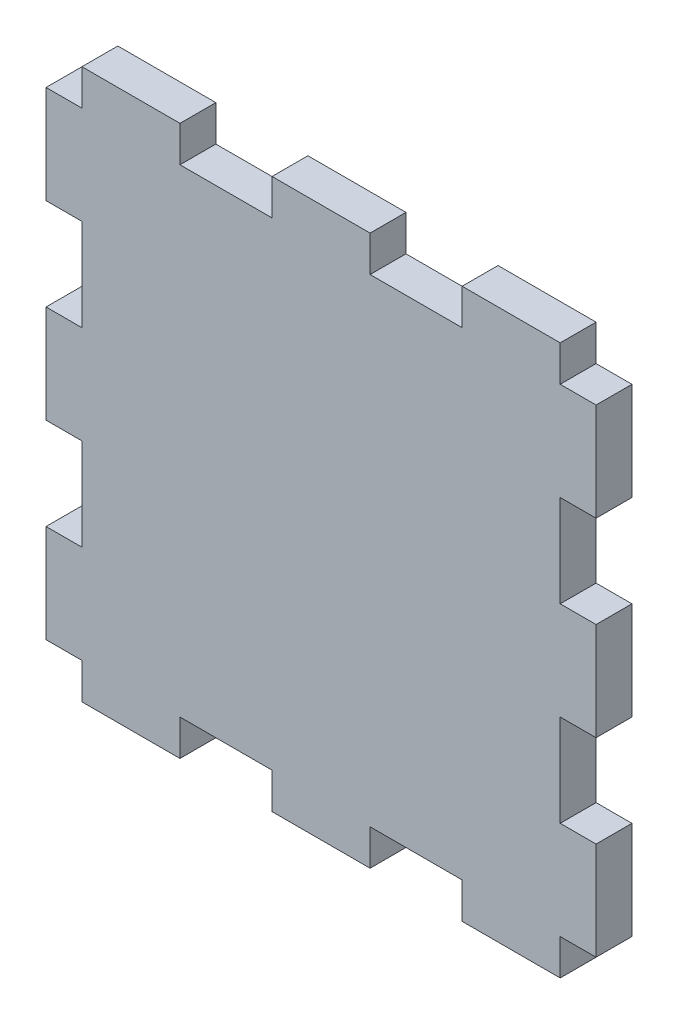
SolidWorks part; units mm, degrees
ref_plane "Alzado" through (0, 0, 0) normal (0, 0, 1) x (1, 0, 0)
ref_plane "Planta" through (0, 0, 0) normal (0, 1, 0) x (1, 0, 0)
ref_plane "Vista lateral" through (0, 0, 0) normal (1, 0, 0) x (0, 0, -1)
sketch "Croquis1" plane through (0, 0, 0) normal (0, 0, 1) x (1, 0, 0)
  line L0 (0, 0) -> (0, 16.0174) construction
  line L1 (20, -20) -> (-20, -20)
  line L2 (20, -20) -> (20, 20)
  line L3 (20, 20) -> (-20, 20)
  line L4 (-20, -20) -> (-20, 20)
  line L5 (20, -20) -> (-20, 20) construction
  line L6 (20, 20) -> (-20, -20) construction
  line L7 (-20, 20) -> (-23, 20)
  line L8 (-20, 20) -> (-20, 11.8)
  line L9 (-20, 11.8) -> (-23, 11.8)
  line L10 (-23, 20) -> (-23, 11.8)
  line L11 (-20, -20) -> (-23, -20)
  line L12 (-20, -20) -> (-20, -11.8)
  line L13 (-20, -11.8) -> (-23, -11.8)
  line L14 (-23, -20) -> (-23, -11.8)
  line L15 (-20, -4.1) -> (-23, -4.1)
  line L16 (-20, -4.1) -> (-20, 4.1)
  line L17 (-20, 4.1) -> (-23, 4.1)
  line L18 (-23, -4.1) -> (-23, 4.1)
  line L19 (-20, -20) -> (-11.8, -20)
  line L20 (-20, -20) -> (-20, -23.0026)
  line L21 (-20, -23.0026) -> (-11.8, -23.0026)
  line L22 (-11.8, -20) -> (-11.8, -23.0026)
  line L23 (-4.1, -20) -> (4.1, -20)
  line L24 (-4.1, -20) -> (-4.1, -23.0026)
  line L25 (-4.1, -23.0026) -> (4.1, -23.0026)
  line L26 (4.1, -20) -> (4.1, -23.0026)
  line L27 (20, -20) -> (11.8, -20)
  line L28 (20, -20) -> (20, -23.0026)
  line L29 (20, -23.0026) -> (11.8, -23.0026)
  line L30 (11.8, -20) -> (11.8, -23.0026)
  line L31 (0, 16.0174) -> (0, 0) construction
  line L32 (0, 0) -> (-15.6024, 0) construction
  line L33 (20, 23.0026) -> (11.8, 23.0026)
  line L34 (11.8, 20) -> (11.8, 23.0026)
  line L35 (20, 20) -> (11.8, 20)
  line L36 (20, 20) -> (20, 23.0026)
  line L37 (-4.1, 23.0026) -> (4.1, 23.0026)
  line L38 (4.1, 20) -> (4.1, 23.0026)
  line L39 (-4.1, 20) -> (4.1, 20)
  line L40 (-4.1, 20) -> (-4.1, 23.0026)
  line L41 (-20, 23.0026) -> (-11.8, 23.0026)
  line L42 (-11.8, 20) -> (-11.8, 23.0026)
  line L43 (-20, 20) -> (-11.8, 20)
  line L44 (-20, 20) -> (-20, 23.0026)
  line L45 (20, -11.8) -> (23, -11.8)
  line L46 (23, -20) -> (23, -11.8)
  line L47 (20, -20) -> (23, -20)
  line L48 (20, -20) -> (20, -11.8)
  line L49 (20, 4.1) -> (23, 4.1)
  line L50 (23, -4.1) -> (23, 4.1)
  line L51 (20, -4.1) -> (23, -4.1)
  line L52 (20, -4.1) -> (20, 4.1)
  line L53 (20, 11.8) -> (23, 11.8)
  line L54 (23, 20) -> (23, 11.8)
  line L55 (20, 20) -> (23, 20)
  line L56 (20, 20) -> (20, 11.8)
  point P0 (0, 0)
  dimension "D1" = 40
  dimension "D2" = 40
  dimension "D3" = 7.7
  dimension "D4" = 8.2
  dimension "D5" = 8.2
  dimension "D6" = 3
  dimension "D7" = 3
  dimension "D8" = 3
  dimension "D9" = 7.7
  dimension "D10" = 8.2
  dimension "D11" = 8.2
  dimension "D12" = 8.2
  dimension "D13" = 7.7
  dimension "D14" = 3.0026
  dimension "D15" = 3.0026
  dimension "D16" = 3.0026
extrude "Saliente-Extruir1" add sketch "Croquis1" along normal blind 3 contours L7 L10 L9 L4 | L44 L3 L42 L41 | L40 L3 L38 L37 | L3 L36 L33 L34 | L4 L1 L2 L3 | L2 L51 L50 L49 | L18 L15 L4 L17 | L14 L11 L4 L13 | L22 L1 L20 L21 | L26 L1 L24 L25 | L1 L30 L29 L28 | L2 L47 L46 L45 | L55 L54 L53 L56
